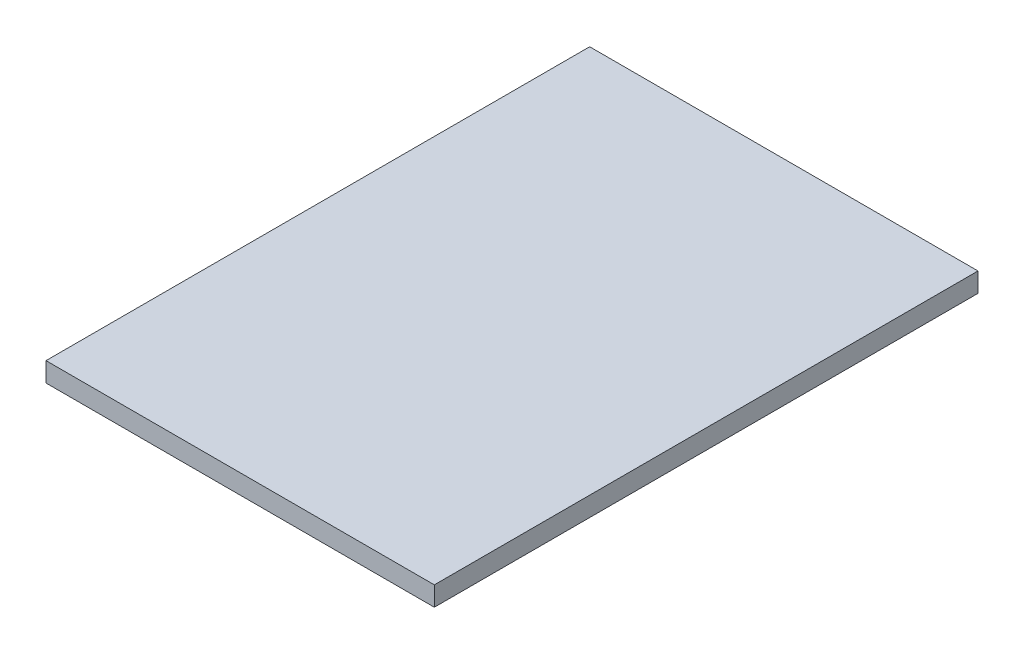
SolidWorks part; units mm, degrees
material "Poplar plywood painted"
ref_plane "Front Plane" through (0, 0, 0) normal (0, 0, 1) x (1, 0, 0)
ref_plane "Top Plane" through (0, 0, 0) normal (0, 1, 0) x (1, 0, 0)
ref_plane "Right Plane" through (0, 0, 0) normal (1, 0, 0) x (0, 0, -1)
sketch "Sketch1" plane through (0, 0, 0) normal (0, 1, 0) x (1, 0, 0)
  line L0 (-90, 126) -> (90, -126) construction
  line L1 (-90, 126) -> (90, 126)
  line L2 (-90, 126) -> (-90, -126)
  line L3 (-90, -126) -> (90, -126)
  line L4 (90, 126) -> (90, -126)
  dimension "D1" = 180
  dimension "D2" = 252
extrude "Boss-Extrude1" add sketch "Sketch1" along normal mid plane 9
